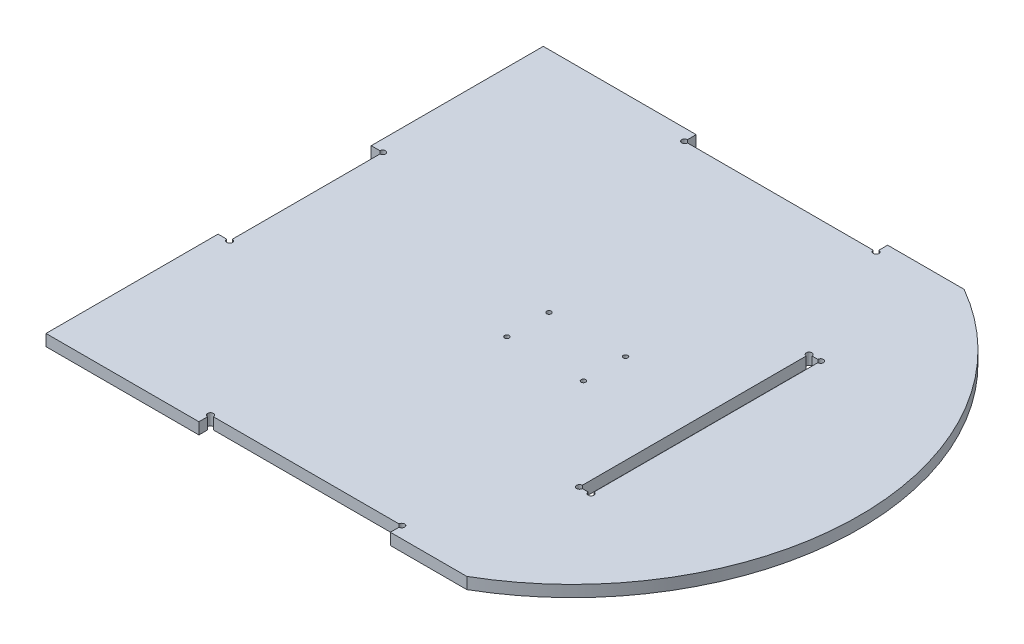
SolidWorks part; units mm, degrees
ref_plane "Front Plane" through (0, 0, 0) normal (0, 0, 1) x (1, 0, 0)
ref_plane "Top Plane" through (0, 0, 0) normal (0, 1, 0) x (1, 0, 0)
ref_plane "Right Plane" through (0, 0, 0) normal (1, 0, 0) x (0, 0, -1)
sketch "Sketch1" plane through (0, 0, 0) normal (0, 1, 0) x (1, 0, 0)
  line L1 (-130, 130) -> (90, 130)
  line L2 (-130, 130) -> (-130, -130)
  line L3 (-130, -130) -> (90, -130)
  line L4 (90, 130) -> (90, -130) construction
  arc A0 (90, 130) -> (90, -130) centre (15.1669, 0) cw
  dimension "D5" = 150
  dimension "D1" = 90
  dimension "D2" = 130
  dimension "D3" = 130
  dimension "D4" = 130
extrude "Boss-Extrude1" add sketch "Sketch1" against normal blind 6
hole_wizard "M2 Clearance Hole1" positions "Sketch2" profile "Sketch3" hole size "M2" standard "ANSI Metric" end condition through all
sketch "Sketch2" plane through (0, -6, 0) normal (0, -1, 0) x (-1, 0, 0)
  point P0 (-32, -11)
  point P3 (-32, 11)
  point P6 (8, -11)
  point P9 (8, 11)
sketch "Sketch3" plane through (32, -6, 11) normal (1, 0, 0) x (0, 0, -1)
  line L0 (0, 0) -> (0, 6)
  line L1 (0, 6) -> (1.2, 6)
  line L2 (1.2, 6) -> (1.2, 0)
  line L5 (1.2, 0) -> (0, 0)
  line L11 (0, -6.35) -> (0, 107.95) construction
  dimension "Thru Hole Dia." = 2.4
  dimension "Thru Hole Depth" = 6
sketch "Sketch4" plane through (0, -6, 0) normal (0, -1, 0) x (1, 0, 0)
  line L8 (85.05, -60.05) -> (85.05, 60.05)
  line L9 (85.05, 60.05) -> (78.95, 60.05)
  line L10 (78.95, 60.05) -> (78.95, -60.05)
  line L11 (78.95, -60.05) -> (85.05, -60.05)
  line L12 (85.05, -60.05) -> (85.05, 60.05)
  line L13 (85.05, 60.05) -> (78.95, 60.05)
  line L14 (78.95, 60.05) -> (78.95, -60.05)
  line L15 (78.95, -60.05) -> (85.05, -60.05)
  line L20 (-50.05, -130.05) -> (50.05, -130.05)
  line L21 (50.05, -130.05) -> (50.05, -123.95)
  line L22 (50.05, -123.95) -> (-50.05, -123.95)
  line L23 (-50.05, -123.95) -> (-50.05, -130.05)
  line L24 (-50.05, -130.05) -> (50.05, -130.05)
  line L25 (50.05, -130.05) -> (50.05, -123.95)
  line L26 (50.05, -123.95) -> (-50.05, -123.95)
  line L27 (-50.05, -123.95) -> (-50.05, -130.05)
  line L32 (-50.05, 123.95) -> (50.05, 123.95)
  line L33 (50.05, 123.95) -> (50.05, 130.05)
  line L34 (50.05, 130.05) -> (-50.05, 130.05)
  line L35 (-50.05, 130.05) -> (-50.05, 123.95)
  line L36 (-50.05, 123.95) -> (50.05, 123.95)
  line L37 (50.05, 123.95) -> (50.05, 130.05)
  line L38 (50.05, 130.05) -> (-50.05, 130.05)
  line L39 (-50.05, 130.05) -> (-50.05, 123.95)
  line L44 (-130.05, 40.05) -> (-130.05, -40.05)
  line L45 (-130.05, -40.05) -> (-123.95, -40.05)
  line L46 (-123.95, -40.05) -> (-123.95, 40.05)
  line L47 (-123.95, 40.05) -> (-130.05, 40.05)
  line L48 (-130.05, 40.05) -> (-130.05, -40.05)
  line L49 (-130.05, -40.05) -> (-123.95, -40.05)
  line L50 (-123.95, -40.05) -> (-123.95, 40.05)
  line L51 (-123.95, 40.05) -> (-130.05, 40.05)
  dimension "D1" = 0.05
  dimension "D2" = 0.05
  dimension "D3" = 0.05
  dimension "D4" = 0.05
extrude "Cut-Extrude1" cut sketch "Sketch4" against normal up to next
hole_wizard "Ø3.0mm Dowel Hole1" positions "Sketch5" profile "Sketch6" hole size "Ø3.0" standard "ANSI Metric" end condition up to next
sketch "Sketch5" plane through (0, -6, 0) normal (0, -1, 0) x (-1, 0, 0)
  point P0 (-85, 60)
  point P3 (-79, 60)
  point P6 (-78.95, -60.05)
  point P9 (-85, -60)
  point P12 (124, 40)
  point P15 (123.95, -40.05)
  point P18 (50.05, -123.95)
  point P21 (-50, -124)
  point P24 (-50.05, 123.95)
  point P27 (50.05, 123.95)
sketch "Sketch6" plane through (85, -6, -60) normal (1, 0, 0) x (0, 0, -1)
  line L0 (0, 0) -> (0, 6)
  line L1 (0, 6) -> (1.5, 6)
  line L2 (1.5, 6) -> (1.5, 0)
  line L5 (1.5, 0) -> (0, 0)
  line L11 (0, -6.35) -> (0, 107.95) construction
  dimension "Thru Hole Dia." = 3
  dimension "Thru Hole Depth" = 6
